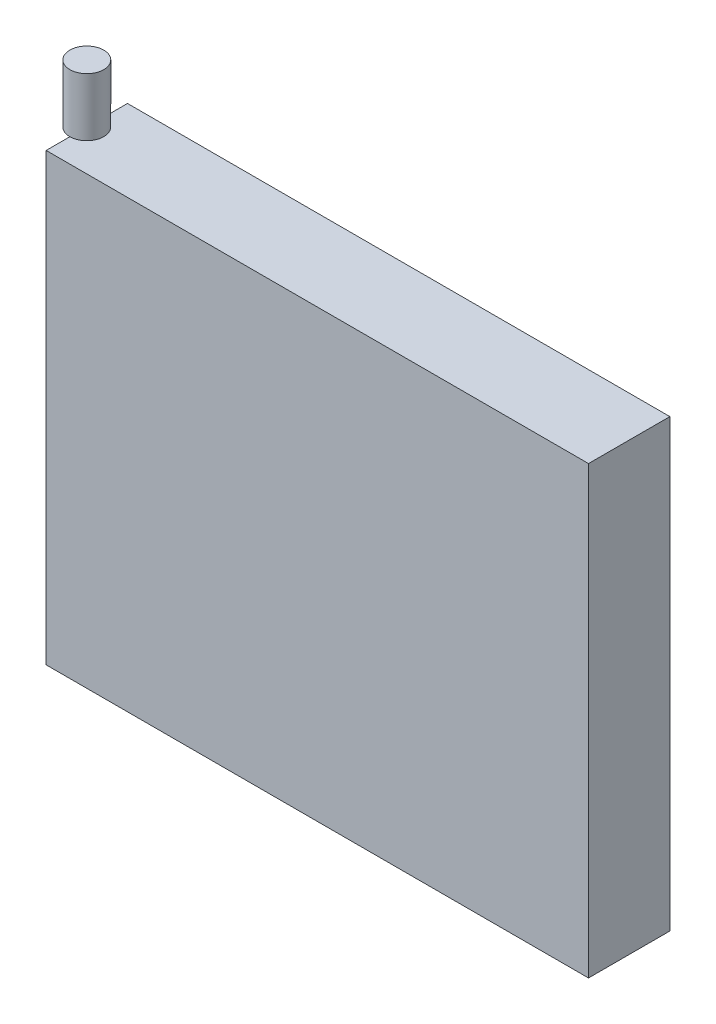
SolidWorks part; units mm, degrees
ref_plane "前视基准面" through (0, 0, 0) normal (0, 0, 1) x (1, 0, 0)
ref_plane "上视基准面" through (0, 0, 0) normal (0, 1, 0) x (1, 0, 0)
ref_plane "右视基准面" through (0, 0, 0) normal (1, 0, 0) x (0, 0, -1)
sketch "草图1" plane through (0, 0, 0) normal (0, 0, 1) x (1, 0, 0)
  line L1 (0, 0) -> (140, 0)
  line L2 (0, 0) -> (0, 115)
  line L3 (0, 115) -> (140, 115)
  line L4 (140, 0) -> (140, 115)
  dimension "D1" = 140
  dimension "D2" = 115
extrude "凸台-拉伸1" add sketch "草图1" along normal blind 21
sketch "草图2" plane through (0, 115, 0) normal (0, 1, 0) x (1, 0, 0)
  line L0 (0, -21) -> (0, 0) construction
  circle A0 centre (0, -10.5) radius 4.3741
extrude "凸台-拉伸2" add sketch "草图2" along normal blind 15
